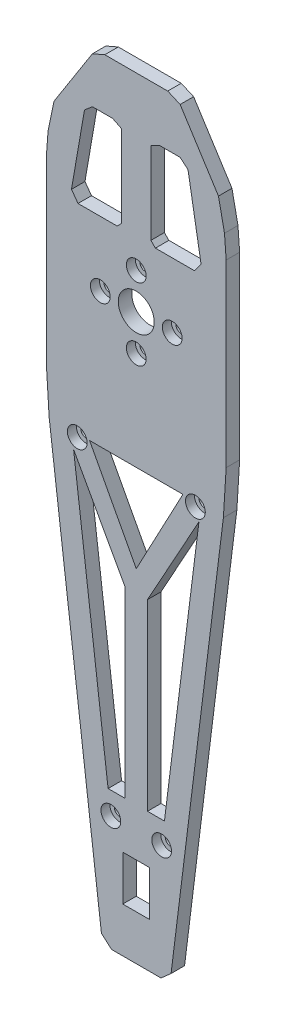
SolidWorks part; units mm, degrees
material "PE High Density"
ref_plane "Front Plane" through (0, 0, 0) normal (0, 0, 1) x (1, 0, 0)
ref_plane "Top Plane" through (0, 0, 0) normal (0, 1, 0) x (1, 0, 0)
ref_plane "Right Plane" through (0, 0, 0) normal (1, 0, 0) x (0, 0, -1)
sketch "Sketch2" plane through (0, 0, 0) normal (0, 0, 1) x (1, 0, 0)
  line L0 (-5.8112, -98.5996) -> (-3.5645, -100.5843)
  line L1 (-5.5645, 100) -> (9.4355, 100)
  line L2 (-18.0645, 45) -> (-18.0645, 5)
  line L3 (-3.5645, -100.5843) -> (7.4355, -100.5843)
  line L4 (21.9355, 45) -> (21.9355, 5)
  line L5 (9.6821, -98.5996) -> (7.4355, -100.5843)
  line L6 (15.1772, 95.0553) -> (9.4355, 100)
  line L7 (-17.3228, 54.9447) -> (-11.3062, 95.0553)
  line L8 (21.1938, 54.9447) -> (15.1772, 95.0553)
  line L9 (-17.4479, -4.9618) -> (-5.8112, -98.5996)
  line L10 (21.3188, -4.9618) -> (9.6821, -98.5996)
  line L11 (-11.3062, 95.0553) -> (-5.5645, 100)
  line L12 (21.9355, 45) -> (21.1938, 54.9447)
  line L13 (21.9355, 5) -> (21.3188, -4.9618)
  line L14 (-18.0645, 5) -> (-17.4479, -4.9618)
  line L15 (-18.0645, 45) -> (-17.3228, 54.9447)
  point P0 (0, 0)
  point P2 (-18.0645, 0)
  point P4 (21.9355, 0)
  point P6 (21.9355, 50)
  point P8 (-18.0645, 50)
  point P9 (-10.5645, 100)
  point P10 (14.4355, 100)
  point P12 (-5.5645, -100.5843)
  point P13 (9.4355, -100.5843)
  dimension "D1" = 7.5
  dimension "D2" = 40
  dimension "D3" = 50
  dimension "D4" = 25
  dimension "D5" = 50
  dimension "D6" = 15
extrude "Boss-Extrude1" add sketch "Sketch2" along normal blind 3
sketch "Sketch3" plane through (0, 0, 3) normal (0, 0, 1) x (1, 0, 0)
  line L0 (21.9355, 5) -> (21.9355, 45) construction
  circle A0 centre (1.9355, 25) radius 4
  dimension "D2" = 8
  dimension "D1" = 20
  dimension "D3" = 25
extrude "Cut-Extrude1" cut sketch "Sketch3" against normal blind 3
hole_wizard "CBORE for M2 SHCS1" positions "Sketch5" profile "Sketch4" counterbore size "M2" standard "Ansi Metric"
sketch "Sketch5" plane through (0, 0, 3) normal (0, 0, 1) x (1, 0, 0)
  circle A0 centre (1.9355, 25) radius 4 construction
  point P0 (1.9355, 33)
  point P1 (9.9355, 25)
  point P3 (1.9355, 17)
  point P5 (-6.0645, 25)
  dimension "D1" = 8
  dimension "D2" = 8
  dimension "D3" = 8
  dimension "D4" = 8
sketch "Sketch4" plane through (1.9355, 33, 3) normal (1, 0, 0) x (0, -1, 0)
  line L0 (0, 0) -> (0, 3.721)
  line L1 (0, 3.721) -> (1.2, 3)
  line L2 (1.2, 3) -> (1.2, 2)
  line L3 (1.2, 2) -> (2.2, 2)
  line L4 (2.2, 2) -> (2.2, 0)
  line L5 (2.2, 0) -> (0, 0)
  line L10 (0, 3.721) -> (-1.2, 3) construction
  line L11 (0, -6.35) -> (0, 107.95) construction
  dimension "Hole Dia." = 2.4
  dimension "Hole Depth" = 3
  dimension "C'Bore Dia." = 4.4
  dimension "C'Bore Depth" = 2
  dimension "Drill Angle" = 118
sketch "Sketch6" plane through (0, 0, 3) normal (0, 0, 1) x (1, 0, 0)
  line L0 (-10.3228, 54.9447) -> (-2.5925, 54.9447)
  line L1 (15.8412, 56.9226) -> (12.5027, 79.1789)
  line L2 (-12.0261, 56.9226) -> (-8.6877, 79.1789)
  line L3 (-4.4175, 94.3136) -> (8.2325, 94.3136)
  line L4 (21.1938, 54.9447) -> (15.1772, 95.0553) construction
  line L5 (-7.3526, 88.0793) -> (-6.7142, 92.3357)
  line L6 (-0.5925, 56.9447) -> (-0.5925, 77.987)
  line L7 (-2.5925, 54.9447) -> (-0.5925, 56.9447)
  line L8 (4.4075, 77.987) -> (4.4075, 56.9447)
  line L9 (11.1676, 88.0793) -> (10.5292, 92.3357)
  line L10 (-6.4131, 80.8601) -> (-2.5704, 80.2837)
  line L11 (-5.6714, 85.8048) -> (1.9075, 84.6679)
  line L12 (1.9075, 84.6679) -> (9.4864, 85.8048)
  line L13 (14.1378, 54.9447) -> (15.8412, 56.9226)
  line L14 (6.3854, 80.2837) -> (10.2282, 80.8601)
  line L15 (-12.0261, 56.9226) -> (-10.3228, 54.9447)
  line L16 (-8.6877, 79.1789) -> (-6.4131, 80.8601)
  line L17 (10.2282, 80.8601) -> (12.5027, 79.1789)
  line L18 (9.4864, 85.8048) -> (11.1676, 88.0793)
  line L19 (-7.3526, 88.0793) -> (-5.6714, 85.8048)
  line L20 (10.5292, 92.3357) -> (8.2325, 94.3136)
  line L21 (-6.7142, 92.3357) -> (-4.4175, 94.3136)
  line L22 (-2.5704, 80.2837) -> (-0.5925, 77.987)
  line L23 (4.4075, 77.987) -> (6.3854, 80.2837)
  line L24 (4.4075, 56.9447) -> (6.4075, 54.9447)
  line L26 (6.4075, 54.9447) -> (14.1378, 54.9447)
  point P0 (-12.3228, 54.9447)
  point P1 (16.1378, 54.9447)
  point P4 (10.2325, 94.3136)
  point P5 (-0.5925, 54.9447)
  point P7 (-6.4175, 94.3136)
  point P9 (-7.6493, 86.1014)
  point P10 (4.4075, 54.9447)
  point P13 (-8.391, 81.1568)
  point P14 (-0.5925, 79.987)
  point P18 (11.4643, 86.1014)
  point P19 (4.4075, 79.987)
  point P20 (12.206, 81.1568)
  point P39 (-0.5925, 54.9447)
  dimension "D1" = 5
  dimension "D2" = 5
extrude "Cut-Extrude2" cut sketch "Sketch6" against normal blind 3
sketch "Sketch7" plane through (0, 0, 3) normal (0, 0, 1) x (1, 0, 0)
  line L0 (1.9355, -100.5843) -> (1.9355, 15.8) construction
  line L1 (-3.5645, -100.5843) -> (7.4355, -100.5843) construction
  line L3 (-1.0645, -80.5843) -> (4.9355, -80.5843)
  line L4 (-1.0645, -80.5843) -> (-1.0645, -90.5843)
  line L5 (-1.0645, -90.5843) -> (4.9355, -90.5843)
  line L6 (4.9355, -80.5843) -> (4.9355, -90.5843)
  line L7 (-1.0645, -80.5843) -> (4.9355, -90.5843) construction
  line L8 (-1.0645, -90.5843) -> (4.9355, -80.5843) construction
  circle A0 centre (1.9355, 17) radius 1.2 construction
  point P7 (1.9355, -85.5843)
  dimension "D1" = 6
  dimension "D2" = 10
  dimension "D3" = 10
extrude "Cut-Extrude3" cut sketch "Sketch7" against normal blind 3
sketch "Sketch8" plane through (0, 0, 3) normal (0, 0, 1) x (1, 0, 0)
  line L0 (-8.4479, -4.9618) -> (12.3188, -4.9618)
  line L1 (15.8807, -8.4709) -> (8.2026, -69.9618)
  line L2 (-12.0097, -8.4709) -> (-4.3316, -69.9618)
  line L3 (-4.3316, -69.9618) -> (-0.5645, -69.9618)
  line L4 (9.6821, -98.5996) -> (21.3188, -4.9618) construction
  line L5 (-17.4479, -4.9618) -> (-5.8112, -98.5996) construction
  line L6 (4.9355, -80.5843) -> (-1.0645, -80.5843) construction
  line L7 (-0.5645, -29.1833) -> (-12.0097, -8.4709)
  line L8 (4.4355, -69.9618) -> (8.2026, -69.9618)
  line L9 (-0.5645, -29.1833) -> (-0.5645, -69.9618)
  line L11 (4.4355, -29.1833) -> (4.4355, -69.9618)
  line L14 (1.9355, -24.4832) -> (-8.4479, -4.9618)
  line L15 (4.4355, -29.1833) -> (15.8807, -8.4709)
  line L16 (12.3188, -4.9618) -> (1.9355, -24.4832)
  point P10 (1.9355, -80.5843)
  point P12 (1.9355, -49.5726)
  dimension "D3" = 65
  dimension "D4" = 5
  dimension "D5" = 5
  dimension "D6" = 5
  dimension "D7" = 2.5
  dimension "D8" = 5
  dimension "D10" = 5
extrude "Cut-Extrude4" cut sketch "Sketch8" against normal blind 3
hole_wizard "CBORE for M2 SHCS2" positions "Sketch11" profile "Sketch10" counterbore size "M2" standard "Ansi Metric"
sketch "Sketch11" plane through (0, 0, 3) normal (0, 0, 1) x (1, 0, 0)
  line L0 (-17.4479, -4.9618) -> (-5.8112, -98.5996) construction
  line L1 (9.6821, -98.5996) -> (21.3188, -4.9618) construction
  line L2 (4.4355, -69.9618) -> (8.2026, -69.9618) construction
  point P0 (-3.715, -74.9237)
  point P1 (7.5812, -74.9618)
  point P11 (-11.1909, -5.6964)
  point P13 (15.0952, -5.9397)
  point P24 (1.9075, 81.1679)
  dimension "D1" = 5
  dimension "D2" = 5
  dimension "D3" = 5
  dimension "D4" = 5
  dimension "D5" = 6.3
  dimension "D6" = 6.3
  dimension "D7" = 3.5
sketch "Sketch10" plane through (-3.715, -74.9237, 3) normal (1, 0, 0) x (0, -1, 0)
  line L0 (0, 0) -> (0, 3.721)
  line L1 (0, 3.721) -> (1.2, 3)
  line L2 (1.2, 3) -> (1.2, 2)
  line L3 (1.2, 2) -> (2.2, 2)
  line L4 (2.2, 2) -> (2.2, 0)
  line L5 (2.2, 0) -> (0, 0)
  line L10 (0, 3.721) -> (-1.2, 3) construction
  line L11 (0, -6.35) -> (0, 107.95) construction
  dimension "Hole Dia." = 2.4
  dimension "Hole Depth" = 3
  dimension "C'Bore Dia." = 4.4
  dimension "C'Bore Depth" = 2
  dimension "Drill Angle" = 118
sketch "Croquis2" plane through (0, 0, 0) normal (0, 0, 1) x (1, 0, 0)
  line L0 (-10.3228, 54.9447) -> (18.7946, 54.9447)
  line L1 (18.7946, 54.9447) -> (-14.9444, 54.9447)
  line L2 (-14.9444, 54.9447) -> (-7.4789, 96.2675)
  line L3 (-7.4789, 96.2675) -> (12.1436, 96.2675)
  line L4 (12.1436, 96.2675) -> (18.7946, 54.9447)
extrude "Saliente-Extruir2" add sketch "Croquis2" along normal blind 3 contours L1 L2 L3 L4
sketch "Croquis3" plane through (0, 0, 0) normal (0, 0, 1) x (1, 0, 0)
  line L0 (-6.3228, 54.9447) -> (10.1938, 54.9447)
  line L1 (1.9355, 75) -> (-0.0645, 75)
  line L2 (-11.3228, 54.9447) -> (-5.3062, 95.0553)
  line L3 (-5.3062, 95.0553) -> (9.1772, 95.0553)
  line L4 (9.1772, 95.0553) -> (15.1938, 54.9447)
  line L5 (15.1938, 54.9447) -> (10.1938, 54.9447)
  line L6 (3.9355, 75) -> (3.9355, 95.0553)
  line L7 (-0.0645, 75) -> (-0.0645, 95.0553)
  line L8 (1.9355, 75) -> (3.9355, 75)
  line L10 (-0.0645, 75) -> (-11.3228, 54.9447)
  line L11 (3.9355, 75) -> (15.1938, 54.9447)
  line L12 (-11.3228, 54.9447) -> (-6.3228, 54.9447)
  line L13 (-6.3228, 54.9447) -> (1.9355, 67.3927)
  line L14 (1.9355, 67.3927) -> (10.1938, 54.9447)
extrude "Cortar-Extruir2" cut sketch "Croquis3" along normal blind 25 contours L6 L11 L4 L3 | L10 L7 L3 L2 | L14 L13 L0
sketch "Croquis4" plane through (0, 0, 0) normal (0, 0, 1) x (1, 0, 0)
  line L0 (0, 74.9459) -> (20.3371, 74.9459)
  line L1 (20.3371, 74.9459) -> (-16.6812, 74.9459)
  line L2 (-16.6812, 74.9459) -> (-16.6812, 106.0261)
  line L3 (-16.6812, 106.0261) -> (20.3371, 106.0261)
  line L4 (20.3371, 106.0261) -> (20.3371, 74.9459)
extrude "Cortar-Extruir3" cut sketch "Croquis4" along normal blind 8 and the other way blind 1 contours L4 L3 L2 L1 L0
sketch "Croquis5" plane through (0, 0, 0) normal (0, 0, 1) x (1, 0, 0)
  line L0 (-14.3226, 74.9459) -> (18.1936, 74.9459)
  line L1 (18.1936, 74.9459) -> (18.1936, 53.9507)
  line L2 (18.1936, 53.9507) -> (-16.1611, 53.9507)
  line L3 (-16.1611, 53.9507) -> (-14.3226, 74.9459)
extrude "Saliente-Extruir3" add sketch "Croquis5" along normal blind 3
sketch "Croquis8" plane through (0, 0, 0) normal (0, 0, 1) x (1, 0, 0)
  line L0 (-14.3226, 74.9459) -> (-15.3726, 67.9459)
  line L1 (-14.3226, 74.9459) -> (-17.3228, 54.9447) construction
  line L2 (-14.3226, 74.9459) -> (-9.3226, 74.9459)
  line L3 (18.1936, 74.9459) -> (-14.3226, 74.9459) construction
  line L4 (-9.3226, 74.9459) -> (-15.3726, 67.9459)
  line L5 (18.1936, 74.9459) -> (13.1936, 74.9459)
  line L6 (18.1936, 74.9459) -> (19.2436, 67.9459)
  line L7 (21.1938, 54.9447) -> (18.1936, 74.9459) construction
  line L8 (19.2436, 67.9459) -> (13.1936, 74.9459)
  dimension "D1" = 7
  dimension "D2" = 5
  dimension "D3" = 5
extrude "Cortar-Extruir4" cut sketch "Croquis8" against normal blind 3 and the other way blind 32
sketch "Croquis9" plane through (0, 0, 0) normal (0, 0, 1) x (1, 0, 0)
  line L0 (-9.3226, 67.9459) -> (-9.3226, 70.9124)
  line L2 (-9.3226, 70.9124) -> (13.1936, 70.9124)
  line L3 (13.1936, 70.9124) -> (13.1936, 67.9459)
  line L4 (-9.3226, 67.9459) -> (-9.3226, 64.3266)
  line L5 (-9.3226, 64.3266) -> (13.1936, 64.3266)
  line L6 (13.1936, 64.3266) -> (13.1936, 67.9459)
extrude "Cortar-Extruir5" cut sketch "Croquis9" against normal blind 16 and the other way blind 33
sketch "Croquis10" plane through (0, 0, 0) normal (0, 0, 1) x (1, 0, 0)
  line L5 (-9.3226, 39.4154) -> (-1.3226, 39.4154)
  line L6 (-9.3226, 39.4154) -> (-9.3226, 59.6587)
  line L7 (-9.3226, 59.6587) -> (-1.3226, 59.6587)
  line L8 (-1.3226, 39.4154) -> (-1.3226, 59.6587)
  line L9 (13.1936, 39.4154) -> (5.1936, 39.4154)
  line L10 (13.1936, 39.4154) -> (13.1936, 59.6587)
  line L11 (13.1936, 59.6587) -> (5.1936, 59.6587)
  line L12 (5.1936, 39.4154) -> (5.1936, 59.6587)
extrude "Cortar-Extruir6" cut sketch "Croquis10" along normal blind 36 and the other way blind 57
sketch "Croquis11" plane through (0, 0, 0) normal (0, 0, 1) x (1, 0, 0)
  line L1 (-9.3226, 70.9124) -> (13.1936, 70.9124)
  line L2 (-9.3226, 70.9124) -> (-9.3226, 64.3266)
  line L3 (-9.3226, 64.3266) -> (13.1936, 64.3266)
  line L4 (13.1936, 70.9124) -> (13.1936, 64.3266)
extrude "Saliente-Extruir4" add sketch "Croquis11" along normal blind 3
sketch "Croquis12" plane through (0, 0, 0) normal (0, 0, 1) x (1, 0, 0)
  line L0 (-9.3226, 74.9459) -> (-5.8226, 74.9459)
  line L1 (13.1936, 74.9459) -> (-9.3226, 74.9459) construction
  line L2 (13.1936, 74.9459) -> (9.6936, 74.9459)
  line L3 (-5.8226, 74.9459) -> (-17.3228, 54.9447)
  line L7 (-17.3228, 54.9447) -> (-15.3726, 67.9459)
  line L8 (-15.3726, 67.9459) -> (-9.3226, 74.9459)
  line L9 (-9.3226, 74.9459) -> (-5.8226, 74.9459)
  dimension "D1" = 3.5
  dimension "D2" = 3.5
extrude "Cortar-Extruir7" cut sketch "Croquis12" along normal blind 12 and the other way blind 26 contours L8 L7 L3 L0
sketch "Croquis13" plane through (0, 0, 0) normal (0, 0, 1) x (1, 0, 0)
  line L0 (13.1936, 74.9459) -> (9.6936, 74.9459)
  line L1 (13.1936, 74.9459) -> (-5.8226, 74.9459) construction
  line L2 (9.6936, 74.9459) -> (21.1938, 54.9447)
  line L3 (21.1938, 54.9447) -> (19.2436, 67.9459)
  line L4 (19.2436, 67.9459) -> (13.1936, 74.9459)
  dimension "D1" = 3.5
extrude "Cortar-Extruir8" cut sketch "Croquis13" against normal blind 23 and the other way blind 37
sketch "Croquis14" plane through (0, 0, 0) normal (0, 0, 1) x (1, 0, 0)
  line L0 (-5.8226, 74.9459) -> (-5.8226, 71.0459)
  line L1 (-5.8226, 74.9459) -> (16.2335, 74.9459)
  line L2 (-5.8226, 74.9459) -> (-5.8226, 71.0504)
  line L3 (16.2335, 74.9459) -> (16.2335, 71.0504)
  line L4 (-5.8226, 71.0504) -> (16.2335, 71.0504)
  dimension "D1" = 3.9
extrude "Cortar-Extruir10" cut sketch "Croquis14" along normal blind 10 and the other way blind 13 contours L0 L4 L3 L1
sketch "Croquis15" plane through (0, 0, 0) normal (0, 0, 1) x (1, 0, 0)
  line L0 (-5.8226, 71.0504) -> (-10.639, 71.0504)
  line L1 (-5.8226, 71.0504) -> (-5.8226, 76.7149)
  line L2 (-10.639, 71.0504) -> (-10.639, 76.7149)
  line L3 (-5.8226, 76.7149) -> (-10.639, 76.7149)
extrude "Cortar-Extruir11" cut sketch "Croquis15" against normal blind 12 and the other way blind 15
sketch "Croquis16" plane through (0, 0, 0) normal (0, 0, 1) x (1, 0, 0)
  line L0 (-8.0624, 71.0504) -> (-7.0624, 71.0504)
  line L1 (-8.0624, 71.0504) -> (11.9334, 71.0504) construction
  line L2 (11.9334, 71.0504) -> (10.9334, 71.0504)
  line L3 (-7.0624, 71.0504) -> (-17.3228, 54.9447)
  line L4 (-17.3228, 54.9447) -> (-8.0624, 71.0504)
  line L5 (10.9334, 71.0504) -> (21.1938, 54.9447)
  line L6 (21.1938, 54.9447) -> (11.9334, 71.0504)
  dimension "D1" = 1
  dimension "D2" = 1
extrude "Cortar-Extruir12" cut sketch "Croquis16" against normal blind 21 and the other way blind 33
sketch "Croquis18" plane through (0, 0, 0) normal (0, 0, 1) x (1, 0, 0)
  line L0 (-7.0624, 71.0504) -> (-5.0624, 71.0504)
  line L1 (-7.0624, 71.0504) -> (10.9334, 71.0504) construction
  line L2 (-7.0624, 71.0504) -> (-7.8269, 69.8504)
  line L3 (-7.0624, 71.0504) -> (-17.3228, 54.9447) construction
  line L4 (-5.0624, 71.0504) -> (-7.8269, 69.8504)
  line L5 (10.9334, 71.0504) -> (8.9334, 71.0504)
  line L6 (10.9334, 71.0504) -> (11.6979, 69.8504)
  line L7 (21.1938, 54.9447) -> (10.9334, 71.0504) construction
  line L8 (11.6979, 69.8504) -> (8.9334, 71.0504)
  dimension "D1" = 2
  dimension "D2" = 1.2
  dimension "D3" = 2
  dimension "D4" = 1.2
extrude "Cortar-Extruir18" cut sketch "Croquis18" along normal blind 52 and the other way blind 75
sketch "Croquis20" plane through (0, 0, 0) normal (0, 0, 1) x (1, 0, 0)
  line L0 (21.1938, 54.9447) -> (20.2266, 56.4628)
  line L1 (21.1938, 54.9447) -> (11.6979, 69.8504) construction
  line L2 (21.1938, 54.9447) -> (21.5646, 49.9723)
  line L3 (21.9355, 45) -> (21.1938, 54.9447) construction
  line L4 (21.5646, 49.9723) -> (20.2266, 56.4628)
  line L6 (-17.3228, 54.9447) -> (-16.3557, 56.4628)
  line L7 (-7.8269, 69.8504) -> (-17.3228, 54.9447) construction
  line L8 (-17.3228, 54.9447) -> (-17.6937, 49.9723)
  line L9 (-17.3228, 54.9447) -> (-18.0645, 45) construction
  line L10 (-16.3557, 56.4628) -> (-17.6937, 49.9723)
  dimension "D1" = 1.8
  dimension "D2" = 1.8
extrude "Cortar-Extruir19" cut sketch "Croquis20" against normal blind 67 and the other way blind 24
sketch "Croquis21" plane through (0, 0, 0) normal (0, 0, 1) x (1, 0, 0)
  line L0 (-9.3226, 39.4154) -> (-12.8226, 39.4154)
  line L1 (13.1936, 39.4154) -> (16.6936, 39.4154)
  line L2 (-12.8226, 39.4154) -> (-9.3226, 59.6587)
  line L3 (-9.3226, 59.6587) -> (-9.3226, 39.4154)
  line L4 (13.1936, 39.4154) -> (13.1936, 59.6587)
  line L5 (13.1936, 59.6587) -> (16.6936, 39.4154)
  dimension "D1" = 3.5
  dimension "D2" = 3.5
extrude "Cortar-Extruir20" cut sketch "Croquis21" against normal blind 62 and the other way blind 39
sketch "Croquis23" plane through (0, 0, 0) normal (0, 0, 1) x (1, 0, 0)
  line L0 (-9.3226, 59.6587) -> (-7.8226, 59.6587)
  line L1 (-1.3226, 59.6587) -> (-9.3226, 59.6587) construction
  line L2 (-9.3226, 59.6587) -> (-9.582, 58.1587)
  line L3 (-12.8226, 39.4154) -> (-9.3226, 59.6587) construction
  line L4 (13.1936, 59.6587) -> (11.6936, 59.6587)
  line L5 (13.1936, 59.6587) -> (5.1936, 59.6587) construction
  line L6 (13.1936, 59.6587) -> (13.4529, 58.1587)
  line L7 (13.1936, 59.6587) -> (16.6936, 39.4154) construction
  line L8 (-9.582, 58.1587) -> (-7.8226, 59.6587)
  line L9 (-9.3226, 59.6587) -> (-9.582, 58.1587)
  line L10 (13.4529, 58.1587) -> (13.1936, 59.6587)
  line L11 (11.6936, 59.6587) -> (13.4529, 58.1587)
  dimension "D1" = 1.5
  dimension "D2" = 1.5
  dimension "D3" = 1.5
  dimension "D4" = 1.5
extrude "Saliente-Extruir7" add sketch "Croquis23" along normal blind 3 contours L2 L8 L0 | L4 L11 L6
sketch "Croquis24" plane through (0, 0, 0) normal (0, 0, 1) x (1, 0, 0)
  line L0 (-1.3226, 39.4154) -> (-1.3226, 40.4154)
  line L1 (-1.3226, 39.4154) -> (-1.3226, 59.6587) construction
  line L2 (-1.3226, 39.4154) -> (-2.3226, 39.4154)
  line L3 (-12.8226, 39.4154) -> (-1.3226, 39.4154) construction
  line L4 (5.1936, 39.4154) -> (6.1936, 39.4154)
  line L5 (5.1936, 39.4154) -> (16.6936, 39.4154) construction
  line L6 (5.1936, 39.4154) -> (5.1936, 40.4154)
  line L7 (5.1936, 59.6587) -> (5.1936, 39.4154) construction
  line L8 (-12.8226, 39.4154) -> (-11.0226, 39.4154)
  line L9 (-12.8226, 39.4154) -> (-12.4768, 41.4154)
  line L10 (-12.8226, 39.4154) -> (-9.582, 58.1587) construction
  line L11 (16.6936, 39.4154) -> (16.3478, 41.4154)
  line L12 (13.4529, 58.1587) -> (16.6936, 39.4154) construction
  line L13 (16.6936, 39.4154) -> (14.8936, 39.4154)
  line L14 (-12.4768, 41.4154) -> (-12.8226, 39.4154)
  line L15 (-11.0226, 39.4154) -> (-12.4768, 41.4154)
  line L16 (-1.3226, 40.4154) -> (-2.3226, 39.4154)
  line L17 (-1.3226, 39.4154) -> (-1.3226, 40.4154)
  line L18 (5.1936, 40.4154) -> (5.1936, 39.4154)
  line L19 (6.1936, 39.4154) -> (5.1936, 40.4154)
  line L20 (16.3478, 41.4154) -> (16.6936, 39.4154)
  line L21 (14.8936, 39.4154) -> (16.3478, 41.4154)
  dimension "D1" = 2
  dimension "D2" = 1.8
  dimension "D3" = 1.8
  dimension "D4" = 2
  dimension "D5" = 1
  dimension "D6" = 1
  dimension "D7" = 1
  dimension "D8" = 1
extrude "Saliente-Extruir9" add sketch "Croquis24" along normal blind 3 contours L8 L15 L9 | L0 L16 L2 | L4 L19 L6 | L21 L13 L11
sketch "Croquis25" plane through (0, 0, 0) normal (0, 0, 1) x (1, 0, 0)
  line L0 (-1.3226, 59.6587) -> (-1.3226, 58.6587)
  line L1 (-1.3226, 40.4154) -> (-1.3226, 59.6587) construction
  line L2 (-1.3226, 59.6587) -> (-3.3226, 59.6587)
  line L4 (-1.3226, 59.6587) -> (-7.8226, 59.6587) construction
  line L6 (5.1936, 59.6587) -> (5.1936, 58.6587)
  line L7 (5.1936, 59.6587) -> (5.1936, 40.4154) construction
  line L8 (5.1936, 59.6587) -> (7.1936, 59.6587)
  line L9 (11.6936, 59.6587) -> (5.1936, 59.6587) construction
  line L10 (-1.3226, 58.6587) -> (-3.3226, 59.6587)
  line L11 (-1.3226, 59.6587) -> (-1.3226, 58.6587)
  line L12 (5.1936, 58.6587) -> (7.1936, 59.6587)
  line L13 (5.1936, 59.6587) -> (5.1936, 58.6587)
  dimension "D1" = 1
  dimension "D2" = 2
  dimension "D3" = 2
  dimension "D4" = 1
extrude "Saliente-Extruir10" add sketch "Croquis25" along normal blind 3 contours L6 L12 L8 | L10 L0 L2
